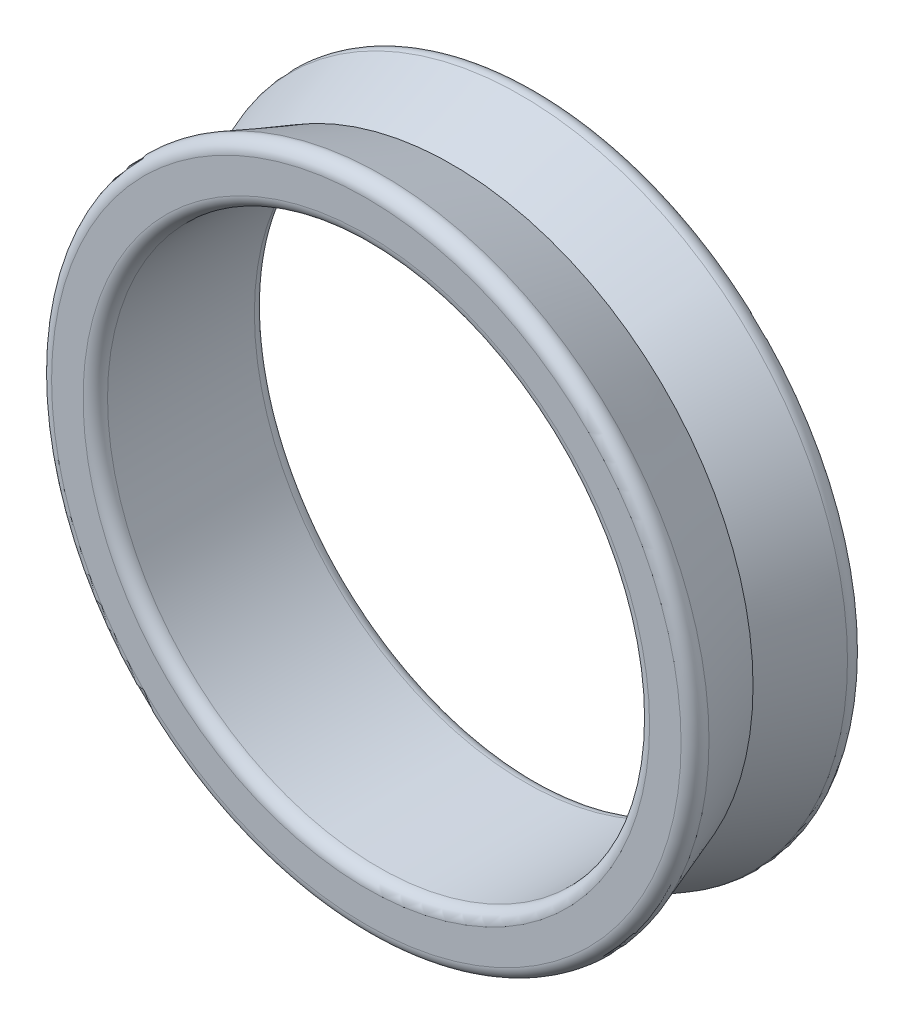
SolidWorks part; units mm, degrees
ref_plane "Front Plane" through (0, 0, 0) normal (0, 0, 1) x (1, 0, 0)
ref_plane "Top Plane" through (0, 0, 0) normal (0, 1, 0) x (1, 0, 0)
ref_plane "Right Plane" through (0, 0, 0) normal (1, 0, 0) x (0, 0, -1)
sketch "Sketch1" plane through (0, 0, 0) normal (0, 0, 1) x (1, 0, 0)
  circle A0 centre (0, 0) radius 11.075
  circle A1 centre (0, 0) radius 13.575
  dimension "D1" = 22.15
  dimension "D2" = 2.5
extrude "Boss-Extrude1" add sketch "Sketch1" along normal blind 7
sketch "Sketch2" plane through (0, 0, 0) normal (0, 1, 0) x (1, 0, 0)
  line L0 (13.575, 0) -> (12.3011, -3.5)
  line L1 (12.3011, -3.5) -> (13.575, -7)
  line L2 (13.575, 0) -> (13.575, -7)
  line L3 (0, 0) -> (0, -5.4003) construction
  dimension "D1" = 20
revolve "Cut-Revolve1" cut sketch "Sketch2" angle 360 about L3
fillet "Fillet1" radius 0.5 2 edges at (-13.575, 0, 7) (-13.575, 0, 0)
fillet "Fillet2" radius 0.5 2 edges at (11.075, 0, 7) (11.075, 0, 0)
